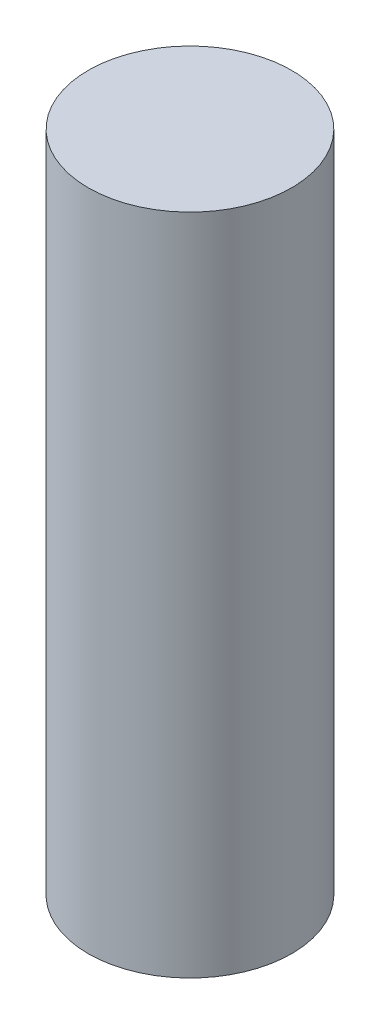
SolidWorks part; units mm, degrees
ref_plane "Front Plane" through (0, 0, 0) normal (0, 0, 1) x (1, 0, 0)
ref_plane "Top Plane" through (0, 0, 0) normal (0, 1, 0) x (1, 0, 0)
ref_plane "Right Plane" through (0, 0, 0) normal (1, 0, 0) x (0, 0, -1)
sketch "Sketch1" plane through (0, 0, 0) normal (0, 1, 0) x (1, 0, 0)
  circle A0 centre (0, 0) radius 6.35
  dimension "D1" = 12.7
extrude "Boss-Extrude1" add sketch "Sketch1" along normal blind 41.402
